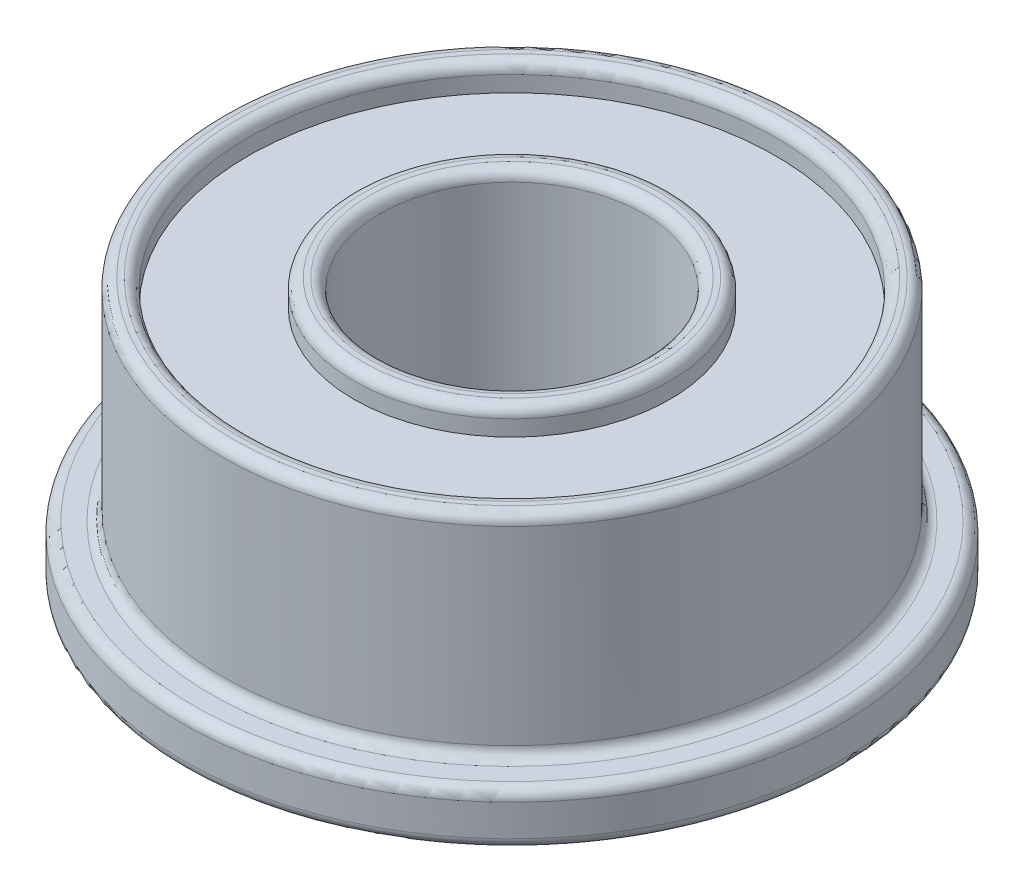
SolidWorks part; units mm, degrees
ref_plane "正面" through (0, 0, 0) normal (0, 0, 1) x (1, 0, 0)
ref_plane "平面" through (0, 0, 0) normal (0, 1, 0) x (1, 0, 0)
ref_plane "右側面" through (0, 0, 0) normal (1, 0, 0) x (0, 0, -1)
sketch "ｽｹｯﾁ1" plane through (0, 0, 0) normal (0, 1, 0) x (1, 0, 0)
  circle A0 centre (0, 0) radius 2.5
  circle A1 centre (0, 0) radius 5.5
  dimension "D1" = 5
  dimension "D2" = 11
extrude "ﾎﾞｽ - 押し出し1" add sketch "ｽｹｯﾁ1" along normal mid plane 5
sketch "ｽｹｯﾁ2" plane through (0, -2.5, 0) normal (0, -1, 0) x (1, 0, 0)
  circle A1 centre (0, 0) radius 5.5
  circle A2 centre (0, 0) radius 5.5
  dimension "D1" = 0
extrude "押し出し-薄板1" add sketch "ｽｹｯﾁ2" against normal blind 1 thin
sketch "ｽｹｯﾁ3" plane through (0, 2.5, 0) normal (0, 1, 0) x (1, 0, 0)
  circle A1 centre (0, 0) radius 2.5 construction
  circle A2 centre (0, 0) radius 5
  circle A3 centre (0, 0) radius 5
  circle A4 centre (0, 0) radius 5.5
  circle A5 centre (0, 0) radius 5.5
  circle A6 centre (0, 0) radius 2.5
  circle A7 centre (0, 0) radius 3
  dimension "D1" = 0.5
  dimension "D2" = 0
  dimension "D3" = 0.5
extrude "ｶｯﾄ - 押し出し1" cut sketch "ｽｹｯﾁ3" against normal mid plane 1 contours A3 A7
mirror "ﾐﾗｰ1" about plane through (0, 0, 0) normal (0, 1, 0) of "ｶｯﾄ - 押し出し1"
fillet "ﾌｨﾚｯﾄ1" radius 0.2 9 edges at (0, -2.5, 5) (0, -2.5, 3) (0, 2.5, 5) (0, 2.5, 3) (6.25, -2.5, 0) (0, -2.5, 2.5) (0, 2.5, 2.5) (0, -1.5, -5.5) (0, 2.5, 5.5)
fillet "ﾌｨﾚｯﾄ2" radius 0.2 1 edges at (6.25, -1.5, 0)
